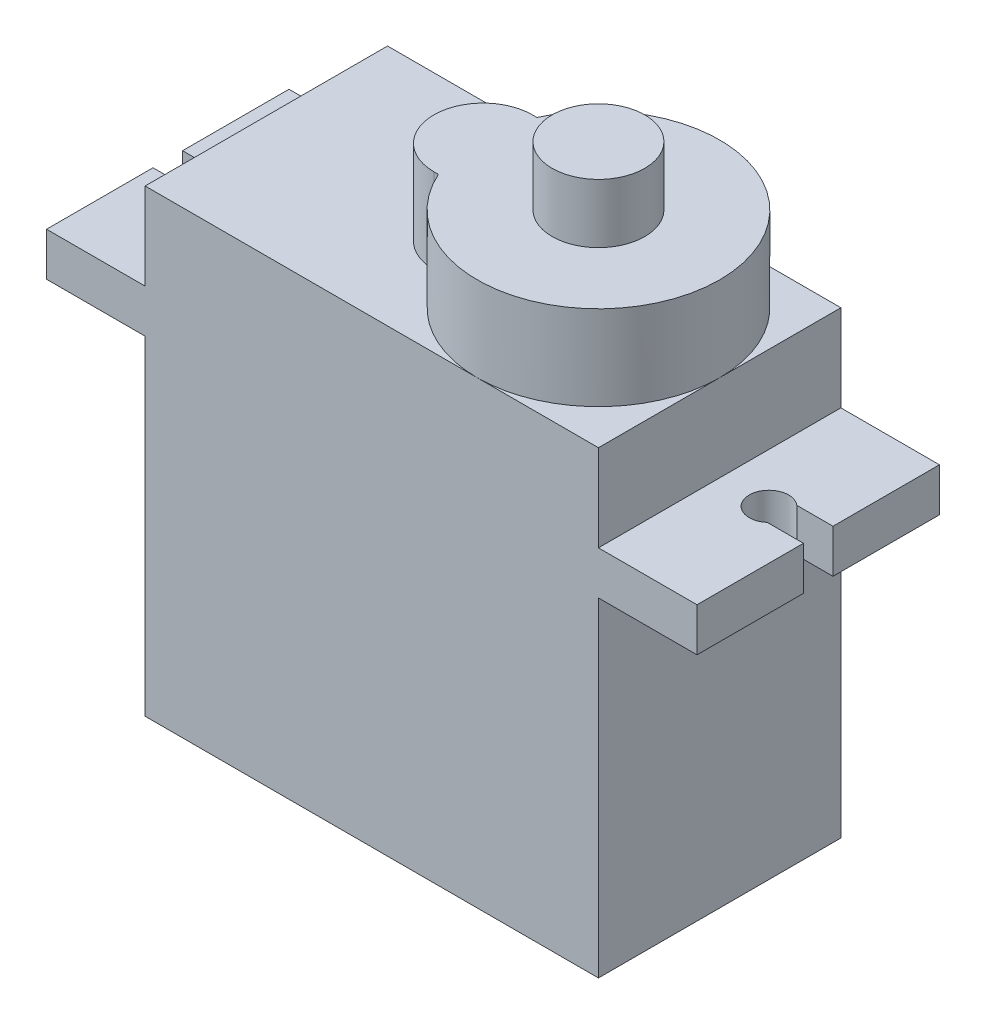
SolidWorks part; units mm, degrees
ref_plane "Спереди" through (0, 0, 0) normal (0, 0, 1) x (1, 0, 0)
ref_plane "Сверху" through (0, 0, 0) normal (0, 1, 0) x (1, 0, 0)
ref_plane "Справа" through (0, 0, 0) normal (1, 0, 0) x (0, 0, -1)
sketch "Эскиз1" plane through (0, 0, 0) normal (0, 1, 0) x (1, 0, 0)
  line L0 (0, 0) -> (23, 0)
  line L1 (23, 0) -> (23, 12.3)
  line L2 (23, 12.3) -> (0, 12.3)
  line L3 (0, 12.3) -> (0, 0)
  line L4 (0, 0) -> (0, 1.0599)
extrude "Бобышка-Вытянуть1" add sketch "Эскиз1" along normal blind 23.3 contours L2 L3 L0 L1
sketch "Эскиз3" plane through (0, 0, 0) normal (0, 0, 1) x (1, 0, 0)
  line L0 (23, 23.3) -> (23, 18.9)
  line L1 (23, 23.3) -> (23, 0) construction
  line L4 (23, 18.9) -> (28, 18.9)
  line L5 (28, 18.9) -> (28, 16.7)
  line L6 (28, 16.7) -> (23, 16.7)
  line L7 (23, 16.7) -> (23, 18.9)
  line M2 (23, 0) -> (23, 23.3)
  dimension "D1" = 5
extrude "Бобышка-Вытянуть2" add sketch "Эскиз3" against normal up to surface (12.3 mm away) contours L6 L5 L4 M2 up to face at (11.5, 11.65, -12.3)
sketch "Эскиз4" plane through (0, 18.9, 0) normal (0, 1, 0) x (1, 0, 0)
  line L0 (28, 6.15) -> (25.5, 6.15) construction
  line L1 (28, 12.3) -> (28, 0) construction
  line L2 (28, 6.15) -> (28, 6.9)
  line L3 (28, 6.15) -> (28, 5.4)
  line L4 (28, 5.4) -> (26.1614, 5.4)
  line L5 (28, 6.9) -> (26.1614, 6.9)
  arc A0 (26.1614, 6.9) -> (26.1614, 5.4) centre (25.5, 6.15) ccw
extrude "Вырез-Вытянуть1" cut sketch "Эскиз4" against normal through all
ref_plane "Плоскость1" through (11.5, 0, 0) normal (-1, 0, 0) x (0, 0, 1)
mirror "Зеркальное отражение2" about plane through (11.5, 0, 0) normal (-1, 0, 0) of "Вырез-Вытянуть1", "Бобышка-Вытянуть2"
sketch "Эскиз5" plane through (0, 23.3, 0) normal (0, 1, 0) x (1, 0, 0)
  line L0 (23, 6.15) -> (8.5, 6.15) construction
  line L1 (11, 3.65) -> (11.2311, 3.65)
  line L2 (23, 12.3) -> (8.3316, -2.3684) construction
  line L3 (23, 0) -> (8.3316, 14.6684) construction
  line L4 (8.5, 6.15) -> (11, 6.15)
  line L5 (11, 8.65) -> (11.2311, 8.65)
  circle A0 centre (16.85, 6.15) radius 6.15
  arc A2 (11, 8.65) -> (11, 3.65) centre (11, 6.15) ccw
extrude "Бобышка-Вытянуть3" add sketch "Эскиз5" along normal blind 4.3
sketch "Эскиз6" plane through (0, 27.6, 0) normal (0, 1, 0) x (1, 0, 0)
  circle A0 centre (16.85, 6.15) radius 2.35
extrude "Бобышка-Вытянуть4" add sketch "Эскиз6" along normal blind 3
ref_plane "Плоскость2" through (0, 16, 0) normal (0, -1, 0) x (-1, 0, 0)
